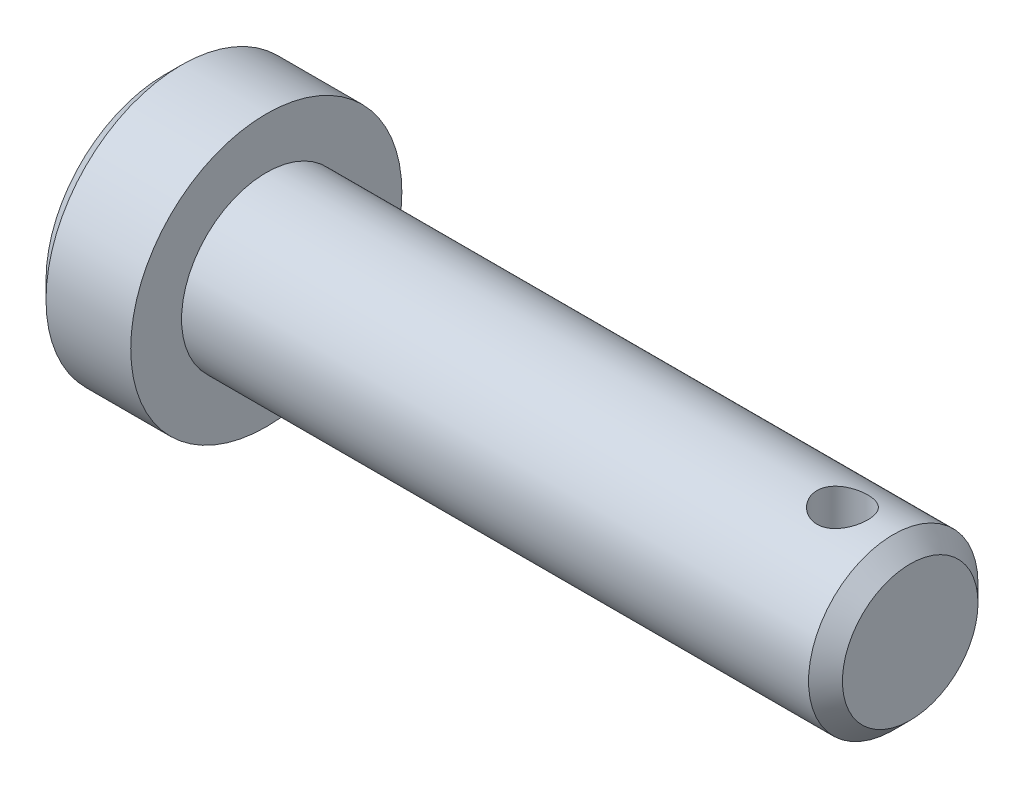
SolidWorks part; units mm, degrees
ref_plane "前视基准面" through (0, 0, 0) normal (0, 0, 1) x (1, 0, 0)
ref_plane "上视基准面" through (0, 0, 0) normal (0, 1, 0) x (1, 0, 0)
ref_plane "右视基准面" through (0, 0, 0) normal (1, 0, 0) x (0, 0, -1)
sketch "草图1" plane through (0, 0, 0) normal (0, 0, 1) x (1, 0, 0)
  line L0 (0, 0) -> (-26.2667, 0) construction
  line L1 (-26.2667, 0) -> (-26.2667, 8)
  line L2 (-26.2667, 8) -> (-20.2667, 8)
  line L3 (-20.2667, 8) -> (-20.2667, 5)
  line L4 (-20.2667, 5) -> (17.7333, 5)
  line L5 (17.7333, 5) -> (17.7333, 0)
  line L6 (-26.2667, 0) -> (17.7333, 0)
  dimension "D1" = 6
  dimension "D2" = 44
  dimension "D3" = 5
  dimension "D4" = 8
revolve "旋转1" add sketch "草图1" angle 360 about L0
chamfer "倒角1" distance 1 angle 45 1 edges at (17.7333, 0, -5)
chamfer "倒角2" distance 1 angle 45 1 edges at (-26.2667, 0, -8)
sketch "草图2" plane through (0, 0, 0) normal (0, 1, 0) x (1, 0, 0)
  line L0 (0, 0) -> (19.9191, 0) construction
  line L1 (16.7333, 5) -> (16.7333, -5) construction
  circle A0 centre (13.7333, 0) radius 1.5
  dimension "D2" = 3
  dimension "D1" = 3
extrude "切除-拉伸2" cut sketch "草图2" against normal through all both and the other way through all contours A0
